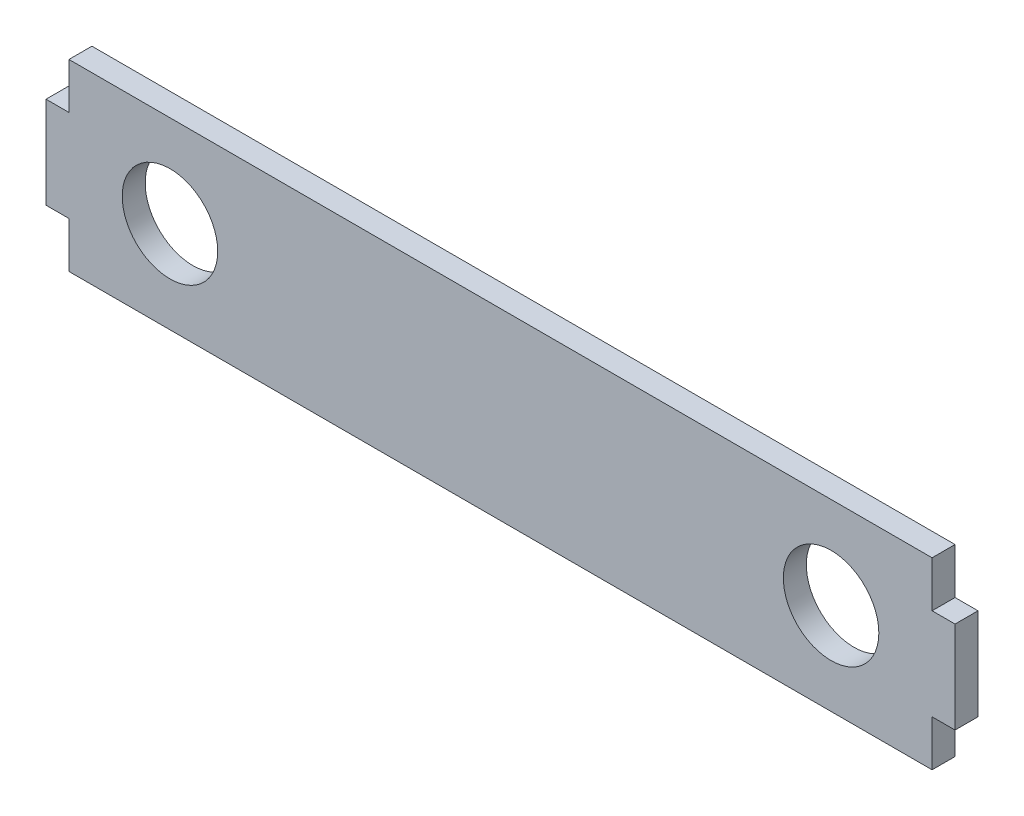
SolidWorks part; units mm, degrees
material "AISI 4130 Steel, annealed at 865C"
ref_plane "X-Y Datum" through (0, 0, 0) normal (0, 0, 1) x (1, 0, 0)
ref_plane "X-Z Datum" through (0, 0, 0) normal (0, 1, 0) x (1, 0, 0)
ref_plane "Y-Z Datum" through (0, 0, 0) normal (1, 0, 0) x (0, 0, -1)
sketch "Sketch1" plane through (0, 0, 0) normal (0, 0, 1) x (1, 0, 0)
  line L0 (31.4325, 0) -> (0, 0) construction
  line L1 (0, 0) -> (0, 6.35) construction
  line L2 (31.4325, -3.175) -> (29.845, -3.175)
  line L3 (29.845, -3.175) -> (29.845, -6.35)
  line L5 (31.4325, 6.35) -> (-31.4325, 6.35)
  line L6 (-31.4325, -6.35) -> (31.4325, -6.35)
  line L16 (31.4325, -6.35) -> (31.4325, 6.35)
  line L17 (-31.4325, 6.35) -> (-31.4325, -6.35)
  line L18 (29.845, 3.175) -> (31.4325, 3.175)
  line L19 (-31.4325, -3.175) -> (-29.845, -3.175)
  line L20 (-29.845, -3.175) -> (-29.845, -6.35)
  line L21 (-29.845, 3.175) -> (-31.4325, 3.175)
  line L22 (29.845, 3.175) -> (29.845, 6.35)
  line L23 (-29.845, 3.175) -> (-29.845, 6.35)
  circle A5 centre (22.86, 0) radius 3.302
  circle A7 centre (-22.86, 0) radius 3.302
  point P4 (0, 0)
  point P8 (0, 0)
  dimension "D5" = 22.86
  dimension "D7" = 6.604
  dimension "D1" = 12.7
  dimension "D2" = 1.5875
  dimension "D3" = 62.865
  dimension "D4" = 6.35
  dimension "D6" = 22.86
extrude "Boss-Extrude1" add sketch "Sketch1" against normal blind 1.5875
